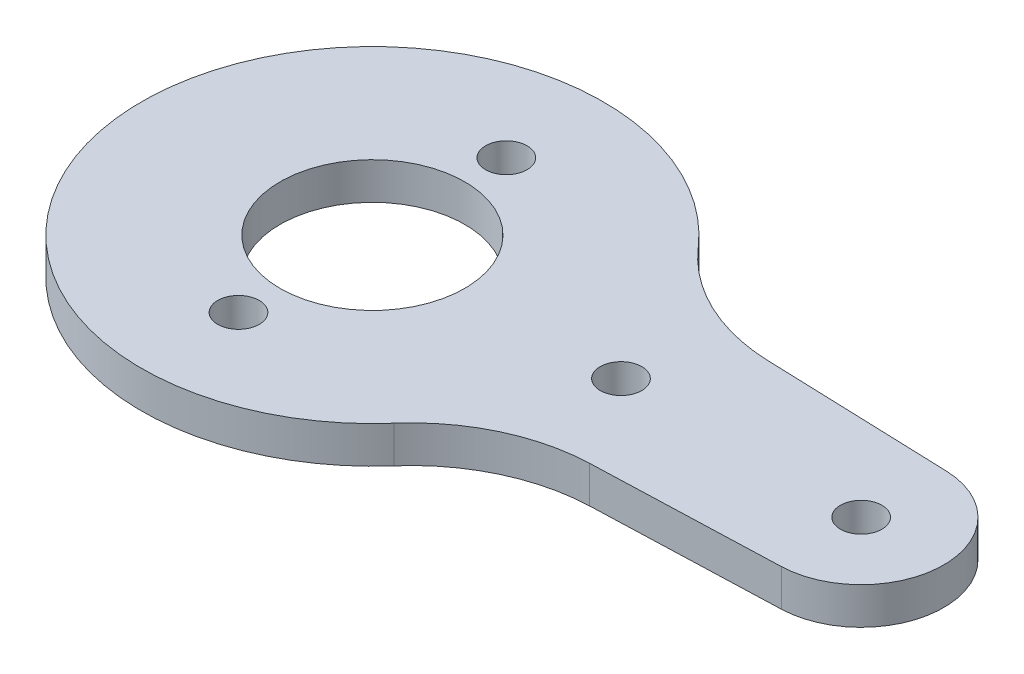
SolidWorks part; units mm, degrees
ref_plane "Front Plane" through (0, 0, 0) normal (0, 0, 1) x (1, 0, 0)
ref_plane "Top Plane" through (0, 0, 0) normal (0, 1, 0) x (1, 0, 0)
ref_plane "Right Plane" through (0, 0, 0) normal (1, 0, 0) x (0, 0, -1)
sketch "Sketch3" plane through (0, 0, 0) normal (0, 1, 0) x (1, 0, 0)
  line L0 (22.9129, 10) -> (53.2251, 8.9415)
  line L8 (53.2251, -8.9415) -> (22.9129, -10)
  line L10 (0, 0) -> (52.9129, 0) construction
  arc A0 (53.2251, 8.9415) -> (53.2251, -8.9415) centre (52.9129, 0) cw
  arc A5 (22.9129, 10) -> (22.9129, -10) centre (0, 0) ccw
  point P0 (0, 0)
  dimension "D1" = 50
  dimension "D3" = 2
  dimension "D4" = 2
  dimension "D5" = 20
  dimension "D7" = 30
extrude "Boss-Extrude1" add sketch "Sketch3" along normal blind 4
fillet "Fillet1" radius 20 2 edges at (22.9129, 2, 10) (22.9129, 2, -10)
sketch "Sketch1" plane through (103.3827, 0, 0) normal (0, 1, 0) x (1, 0, 0)
  line L6 (-103.3827, 14.5) -> (-103.3827, -14.5) construction
  line L16 (-77.868, 0) -> (-103.3827, 0) construction
  circle A6 centre (-103.3827, 0) radius 10
  circle A7 centre (-103.3827, 14.5) radius 2.25
  circle A9 centre (-76.4698, 0) radius 2.25
  circle A16 centre (-50.4698, 0) radius 2.25
  arc A17 (-50.1576, -8.9415) -> (-50.1576, 8.9415) centre (-50.4698, 0) ccw construction
  circle A18 centre (-103.3827, -14.5) radius 2.25
  point P5 (-103.3827, 0)
  dimension "D4" = 4.5
  dimension "D3" = 29
  dimension "D2" = 4.5
  dimension "D1" = 20
  dimension "D7" = 26
extrude "Cut-Extrude3" cut sketch "Sketch1" along normal through all
